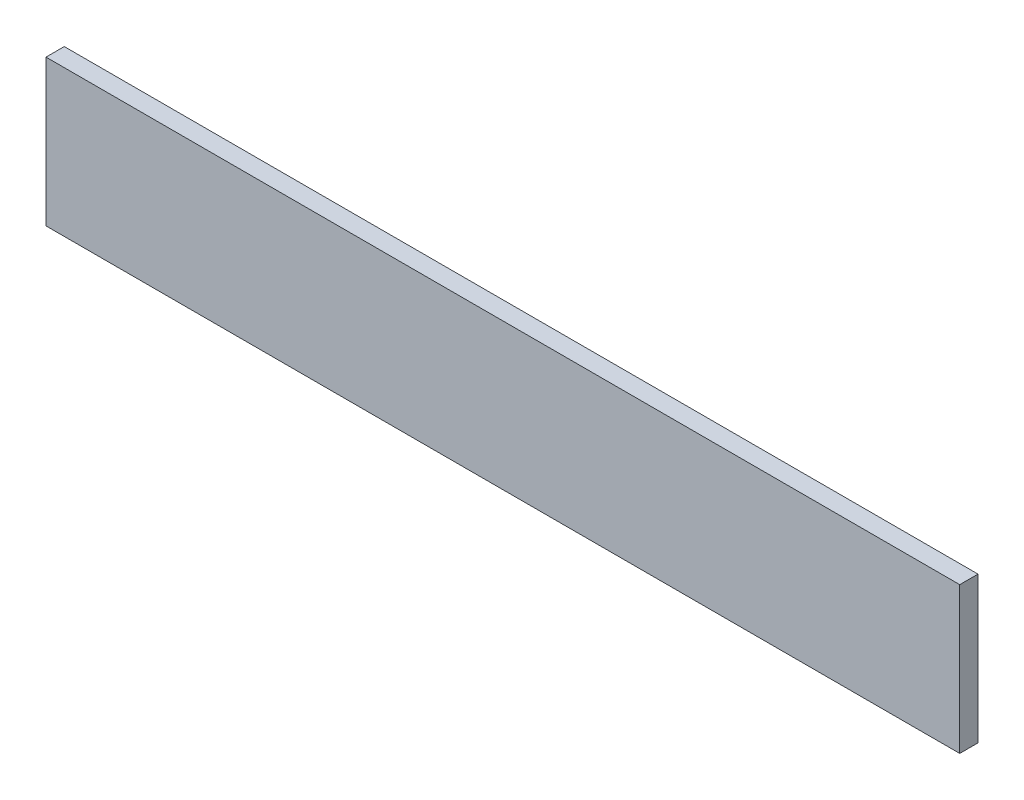
SolidWorks part; units mm, degrees
material "5052-H34"
ref_plane "正面" through (0, 0, 0) normal (0, 0, 1) x (1, 0, 0)
ref_plane "平面" through (0, 0, 0) normal (0, 1, 0) x (1, 0, 0)
ref_plane "右側面" through (0, 0, 0) normal (1, 0, 0) x (0, 0, -1)
sketch "ｽｹｯﾁ1" plane through (0, 0, 0) normal (0, 0, 1) x (1, 0, 0)
  line L1 (-125, 20) -> (125, 20)
  line L2 (-125, 20) -> (-125, -20)
  line L3 (-125, -20) -> (125, -20)
  line L4 (125, 20) -> (125, -20)
  line L5 (-125, 20) -> (125, -20) construction
  line L6 (-125, -20) -> (125, 20) construction
  point P0 (0, 0)
  dimension "D1" = 40
  dimension "D2" = 250
extrude "ﾎﾞｽ - 押し出し1" add sketch "ｽｹｯﾁ1" along normal blind 5
